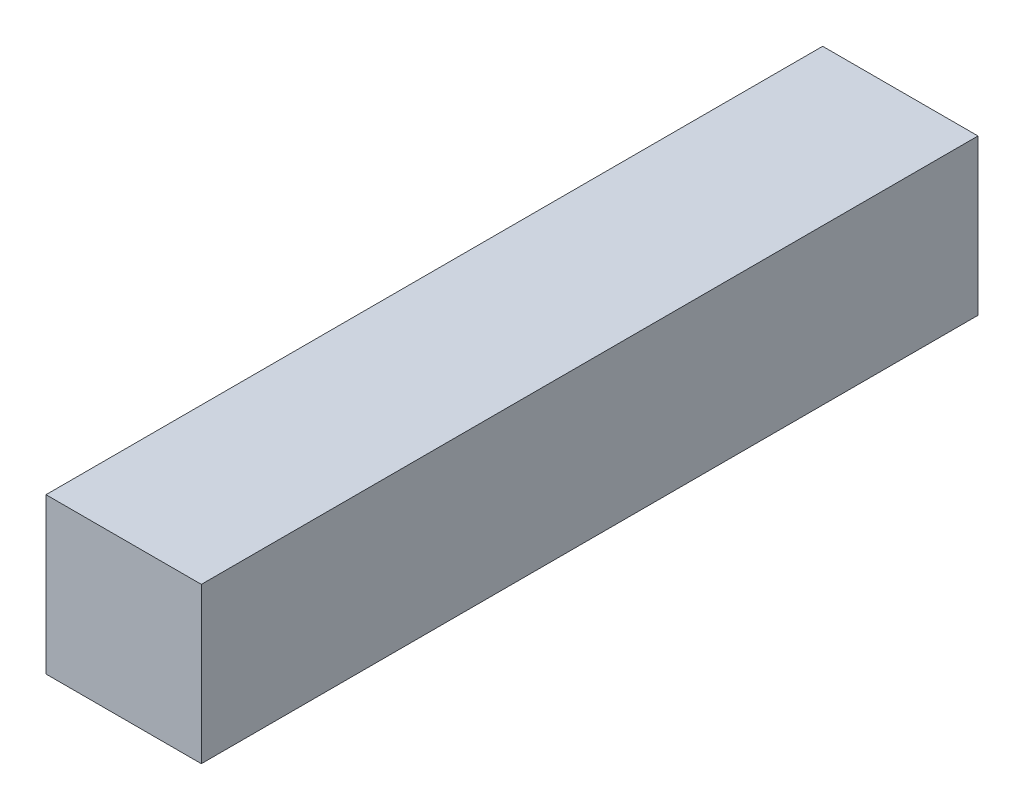
SolidWorks part; units mm, degrees
ref_plane "Front Plane" through (0, 0, 0) normal (0, 0, 1) x (1, 0, 0)
ref_plane "Top Plane" through (0, 0, 0) normal (0, 1, 0) x (1, 0, 0)
ref_plane "Right Plane" through (0, 0, 0) normal (1, 0, 0) x (0, 0, -1)
sketch "Sketch1" plane through (0, 0, 0) normal (0, 0, 1) x (1, 0, 0)
  line L1 (-10, -10) -> (10, -10)
  line L2 (-10, -10) -> (-10, 10)
  line L3 (-10, 10) -> (10, 10)
  line L4 (10, -10) -> (10, 10)
  line L5 (-10, -10) -> (10, 10) construction
  line L6 (-10, 10) -> (10, -10) construction
  point P0 (0, 0)
  dimension "D1" = 20
extrude "Boss-Extrude1" add sketch "Sketch1" along normal blind 100
